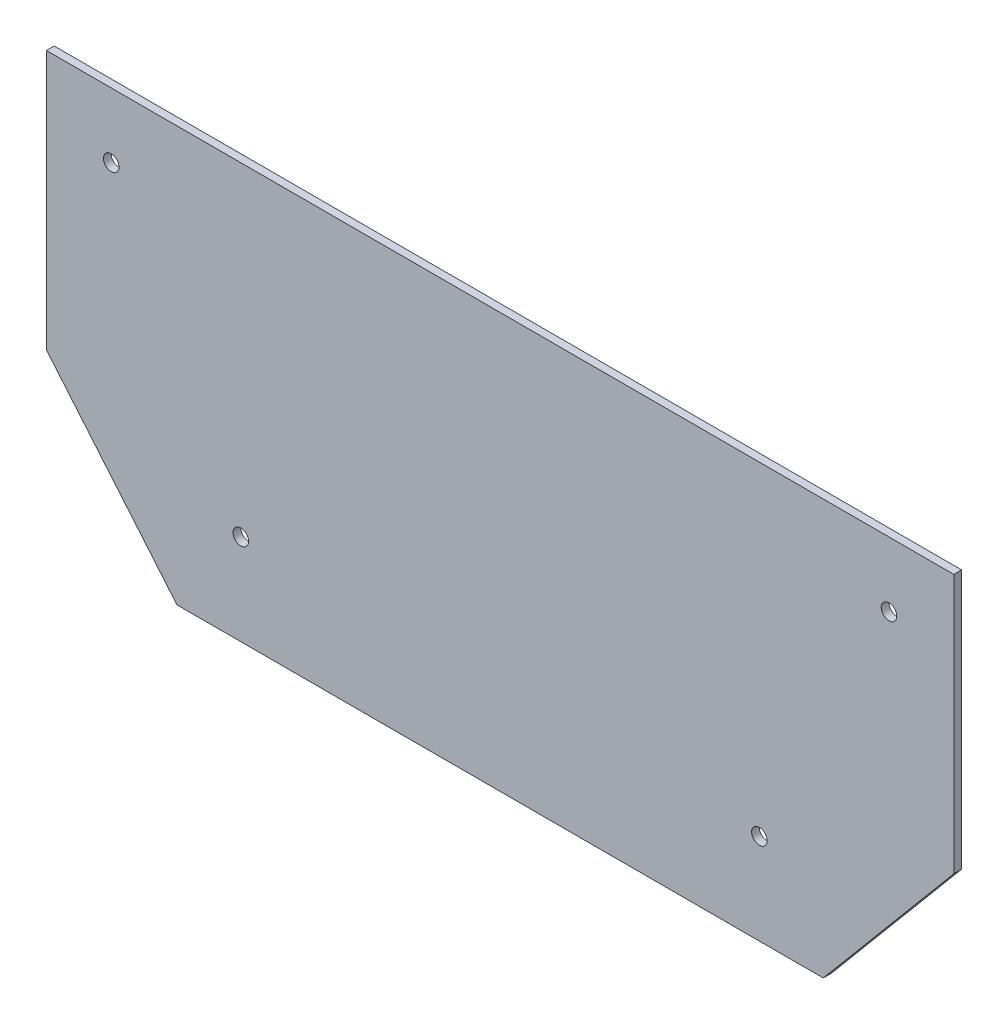
SolidWorks part; units mm, degrees
ref_plane "Front Plane" through (0, 0, 0) normal (0, 0, 1) x (1, 0, 0)
ref_plane "Top Plane" through (0, 0, 0) normal (0, 1, 0) x (1, 0, 0)
ref_plane "Right Plane" through (0, 0, 0) normal (1, 0, 0) x (0, 0, -1)
sketch "Sketch1" plane through (0, 0, 0) normal (0, 0, 1) x (1, 0, 0)
  line L0 (-87.5, 40) -> (87.5, 40)
  line L1 (87.5, 40) -> (87.5, -10)
  line L2 (87.5, -10) -> (62.327, -40)
  line L3 (62.327, -40) -> (-62.327, -40)
  line L4 (-62.327, -40) -> (-87.5, -10)
  line L5 (-87.5, -10) -> (-87.5, 40)
  line L7 (0, 71.9854) -> (0, -71.9854) construction
  circle A0 centre (-75, 27.5) radius 1.5
  circle A1 centre (-50, -22.5) radius 1.5
  circle A2 centre (50, -22.5) radius 1.5
  circle A3 centre (75, 27.5) radius 1.5
  point P18 (0, -40)
  point P22 (0, 0)
  dimension "D1" = 175
  dimension "D2" = 12.5
  dimension "D3" = 12.5
  dimension "D4" = 17.5
  dimension "D5" = 130
  dimension "D6" = 130
  dimension "D7" = 50
extrude "Boss-Extrude1" add sketch "Sketch1" along normal blind 1.5
